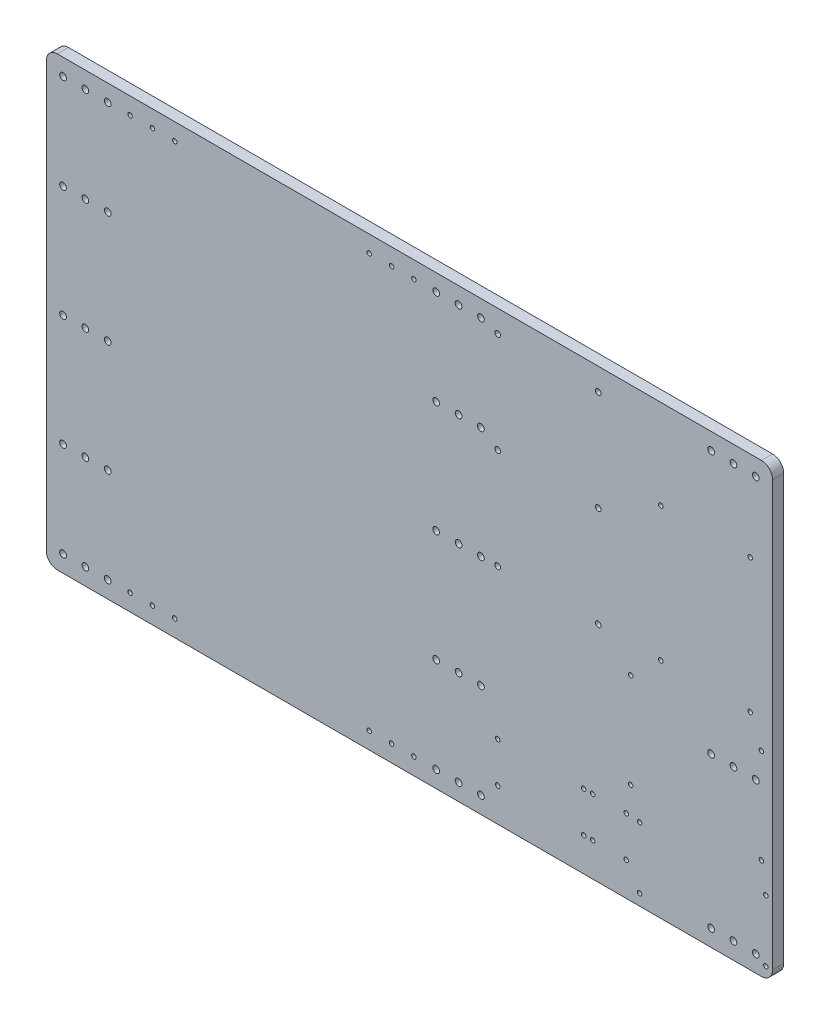
SolidWorks part; units mm, degrees
ref_plane "前视基准面" through (0, 0, 0) normal (0, 0, 1) x (1, 0, 0)
ref_plane "上视基准面" through (0, 0, 0) normal (0, 1, 0) x (1, 0, 0)
ref_plane "右视基准面" through (0, 0, 0) normal (1, 0, 0) x (0, 0, -1)
sketch "草图1" plane through (0, 0, 0) normal (0, 0, 1) x (1, 0, 0)
  line L0 (44, 200) -> (44, -200) construction
  line L1 (-325, -200) -> (325, -200)
  line L2 (-325, -200) -> (-325, 200)
  line L3 (-325, 200) -> (325, 200)
  line L4 (325, -200) -> (325, 200)
  line L5 (-325, -200) -> (325, 200) construction
  line L6 (-325, 200) -> (325, -200) construction
  line L7 (-290, 200) -> (-290, -200) construction
  line L8 (-325, 100) -> (325, 100) construction
  line L9 (-325, 0) -> (325, 0) construction
  line L10 (-325, -100) -> (325, -100) construction
  line L11 (-310, 200) -> (-310, -200) construction
  line L12 (-270, 200) -> (-270, -200) construction
  line L13 (24, 200) -> (24, -200) construction
  line L14 (64, 200) -> (64, -200) construction
  line L15 (79, 200) -> (79, -200) construction
  line L16 (169, 200) -> (169, -200) construction
  line L17 (79, 0) -> (325, 0) construction
  line L18 (325, 180) -> (79, 180) construction
  line L19 (325, 90) -> (79, 90) construction
  line L20 (225, 200) -> (225, -200) construction
  line L21 (305, 200) -> (305, -200) construction
  line L22 (325, 120) -> (225, 120) construction
  line L23 (325, 0) -> (225, 0) construction
  line L24 (325, -134) -> (79, -134) construction
  line L25 (325, -170) -> (79, -170) construction
  line L26 (156, -200) -> (156, -134) construction
  line L27 (164, -134) -> (164, -200) construction
  line L28 (194, -134) -> (194, -200) construction
  line L29 (325, -25) -> (169, -25) construction
  line L30 (325, -110) -> (169, -110) construction
  line L31 (315, -25) -> (315, -110) construction
  line L32 (198, -25) -> (198, -110) construction
  line L33 (206, -110) -> (206, -200) construction
  line L34 (319, -110) -> (319, -200) construction
  line L35 (206, -190) -> (325, -190) construction
  line L36 (206, -135) -> (325, -135) construction
  line L37 (-325, 185) -> (64, 185) construction
  line L38 (-325, -185) -> (64, -185) construction
  line L39 (-16, 200) -> (-16, 185) construction
  line L40 (4, 200) -> (4, 185) construction
  line L41 (-36, 200) -> (-36, 185) construction
  line L42 (-250, 200) -> (-250, 185) construction
  line L43 (-230, 200) -> (-230, 185) construction
  line L44 (-210, 200) -> (-210, 185) construction
  line L45 (-250, -200) -> (-250, -185) construction
  line L46 (-230, -200) -> (-230, -185) construction
  line L47 (-210, -200) -> (-210, -185) construction
  line L48 (4, -200) -> (4, -185) construction
  line L49 (-16, -200) -> (-16, -185) construction
  line L50 (-36, -200) -> (-36, -185) construction
  line L51 (64, -185) -> (325, -185) construction
  line L52 (310, -200) -> (310, -185) construction
  line L53 (290, -200) -> (290, -185) construction
  line L54 (270, -200) -> (270, -185) construction
  line L55 (64, 185) -> (325, 185) construction
  line L56 (310, 200) -> (310, 185) construction
  line L57 (290, 200) -> (290, 185) construction
  line L58 (270, 200) -> (270, 185) construction
  line L59 (270, -185) -> (270, 185) construction
  line L60 (290, -185) -> (290, 185) construction
  line L61 (310, -185) -> (310, 185) construction
  line L62 (270, -50) -> (325, -50) construction
  circle A0 centre (-310, 100) radius 3
  circle A1 centre (-290, 100) radius 3
  circle A2 centre (-270, 100) radius 3
  circle A3 centre (-310, 0) radius 3
  circle A4 centre (-290, 0) radius 3
  circle A5 centre (-270, 0) radius 3
  circle A6 centre (-310, -100) radius 3
  circle A7 centre (-290, -100) radius 3
  circle A8 centre (-270, -100) radius 3
  circle A9 centre (24, 100) radius 3
  circle A10 centre (44, 100) radius 3
  circle A11 centre (64, 100) radius 3
  circle A12 centre (24, -100) radius 3
  circle A13 centre (44, -100) radius 3
  circle A14 centre (64, -100) radius 3
  circle A15 centre (24, 0) radius 3
  circle A16 centre (44, 0) radius 3
  circle A17 centre (64, 0) radius 3
  circle A18 centre (79, 180) radius 2.5
  circle A19 centre (169, 180) radius 2.5
  circle A20 centre (79, 90) radius 2.5
  circle A21 centre (79, 0) radius 2.5
  circle A22 centre (169, 90) radius 2.5
  circle A23 centre (169, 0) radius 2.5
  circle A24 centre (305, 120) radius 2
  circle A25 centre (225, 120) radius 2
  circle A26 centre (305, 0) radius 2
  circle A27 centre (225, 0) radius 2
  circle A28 centre (79, -134) radius 2
  circle A29 centre (79, -170) radius 2
  circle A30 centre (156, -134) radius 2
  circle A31 centre (156, -170) radius 2
  circle A32 centre (164, -134) radius 2
  circle A33 centre (164, -170) radius 2
  circle A34 centre (194, -134) radius 2
  circle A35 centre (194, -170) radius 2
  circle A36 centre (198, -25) radius 2
  circle A37 centre (315, -25) radius 2
  circle A38 centre (198, -110) radius 2
  circle A39 centre (315, -110) radius 2
  circle A40 centre (206, -190) radius 2
  circle A41 centre (206, -135) radius 2
  circle A42 centre (319, -190) radius 2
  circle A43 centre (319, -135) radius 2
  circle A44 centre (-310, -185) radius 3
  circle A45 centre (-290, -185) radius 3
  circle A46 centre (-270, -185) radius 3
  circle A47 centre (24, -185) radius 3
  circle A48 centre (44, -185) radius 3
  circle A49 centre (64, -185) radius 3
  circle A50 centre (-310, 185) radius 3
  circle A51 centre (-290, 185) radius 3
  circle A52 centre (-270, 185) radius 3
  circle A53 centre (24, 185) radius 3
  circle A54 centre (44, 185) radius 3
  circle A55 centre (64, 185) radius 3
  circle A56 centre (-36, 185) radius 2
  circle A57 centre (-16, 185) radius 2
  circle A58 centre (4, 185) radius 2
  circle A59 centre (-250, 185) radius 2
  circle A60 centre (-230, 185) radius 2
  circle A61 centre (-210, 185) radius 2
  circle A62 centre (-250, -185) radius 2
  circle A63 centre (-230, -185) radius 2
  circle A64 centre (-210, -185) radius 2
  circle A65 centre (4, -185) radius 2
  circle A66 centre (-16, -185) radius 2
  circle A67 centre (-36, -185) radius 2
  circle A68 centre (310, -185) radius 3
  circle A69 centre (290, -185) radius 3
  circle A70 centre (270, -185) radius 3
  circle A71 centre (310, 185) radius 3
  circle A73 centre (270, 185) radius 3
  circle A74 centre (290, 185) radius 3
  circle A75 centre (270, -50) radius 3
  circle A76 centre (290, -50) radius 3
  circle A77 centre (310, -50) radius 3
  point P0 (0, 0)
  dimension "D11" = 6
  dimension "D12" = 6
  dimension "D13" = 6
  dimension "D14" = 6
  dimension "D15" = 6
  dimension "D16" = 6
  dimension "D17" = 6
  dimension "D18" = 6
  dimension "D19" = 6
  dimension "D20" = 6
  dimension "D21" = 6
  dimension "D22" = 6
  dimension "D23" = 6
  dimension "D24" = 6
  dimension "D25" = 6
  dimension "D26" = 6
  dimension "D27" = 6
  dimension "D28" = 6
  dimension "D34" = 5
  dimension "D35" = 5
  dimension "D36" = 5
  dimension "D37" = 5
  dimension "D38" = 5
  dimension "D39" = 5
  dimension "D44" = 4
  dimension "D45" = 4
  dimension "D46" = 4
  dimension "D47" = 4
  dimension "D53" = 4
  dimension "D54" = 4
  dimension "D55" = 4
  dimension "D56" = 4
  dimension "D57" = 4
  dimension "D58" = 4
  dimension "D59" = 4
  dimension "D60" = 4
  dimension "D65" = 4
  dimension "D66" = 4
  dimension "D67" = 4
  dimension "D68" = 4
  dimension "D73" = 4
  dimension "D74" = 4
  dimension "D75" = 4
  dimension "D76" = 4
  dimension "D79" = 6
  dimension "D80" = 6
  dimension "D81" = 6
  dimension "D82" = 6
  dimension "D83" = 6
  dimension "D84" = 6
  dimension "D85" = 6
  dimension "D86" = 6
  dimension "D87" = 6
  dimension "D88" = 6
  dimension "D89" = 6
  dimension "D90" = 6
  dimension "D94" = 4
  dimension "D95" = 4
  dimension "D96" = 4
  dimension "D100" = 4
  dimension "D101" = 4
  dimension "D102" = 4
  dimension "D106" = 4
  dimension "D107" = 4
  dimension "D108" = 4
  dimension "D112" = 4
  dimension "D113" = 4
  dimension "D114" = 4
  dimension "D118" = 6
  dimension "D119" = 6
  dimension "D120" = 6
  dimension "D124" = 6
  dimension "D125" = 6
  dimension "D126" = 6
  dimension "D128" = 6
  dimension "D129" = 6
  dimension "D130" = 6
  dimension "D1" = 400
  dimension "D2" = 650
  dimension "D3" = 20
  dimension "D4" = 20
  dimension "D5" = 294
  dimension "D6" = 20
  dimension "D7" = 20
  dimension "D8" = 15
  dimension "D9" = 100
  dimension "D10" = 100
  dimension "D29" = 90
  dimension "D30" = 15
  dimension "D31" = 90
  dimension "D32" = 90
  dimension "D33" = 20
  dimension "D40" = 80
  dimension "D41" = 20
  dimension "D42" = 80
  dimension "D43" = 120
  dimension "D48" = 36
  dimension "D49" = 77
  dimension "D50" = 8
  dimension "D51" = 30
  dimension "D52" = 30
  dimension "D61" = 85
  dimension "D62" = 117
  dimension "D63" = 10
  dimension "D64" = 25
  dimension "D69" = 113
  dimension "D70" = 55
  dimension "D71" = 12
  dimension "D72" = 10
  dimension "D77" = 15
  dimension "D78" = 15
  dimension "D91" = 20
  dimension "D92" = 20
  dimension "D93" = 20
  dimension "D97" = 20
  dimension "D98" = 20
  dimension "D99" = 20
  dimension "D103" = 20
  dimension "D104" = 20
  dimension "D105" = 20
  dimension "D109" = 20
  dimension "D110" = 20
  dimension "D111" = 20
  dimension "D115" = 15
  dimension "D116" = 20
  dimension "D117" = 20
  dimension "D121" = 15
  dimension "D122" = 20
  dimension "D123" = 20
  dimension "D127" = 60
extrude "凸台-拉伸1" add sketch "草图1" along normal blind 10
fillet "圆角1" radius 10 4 edges at (-325, -200, 5) (325, -200, 5) (325, 200, 5) (-325, 200, 5)
